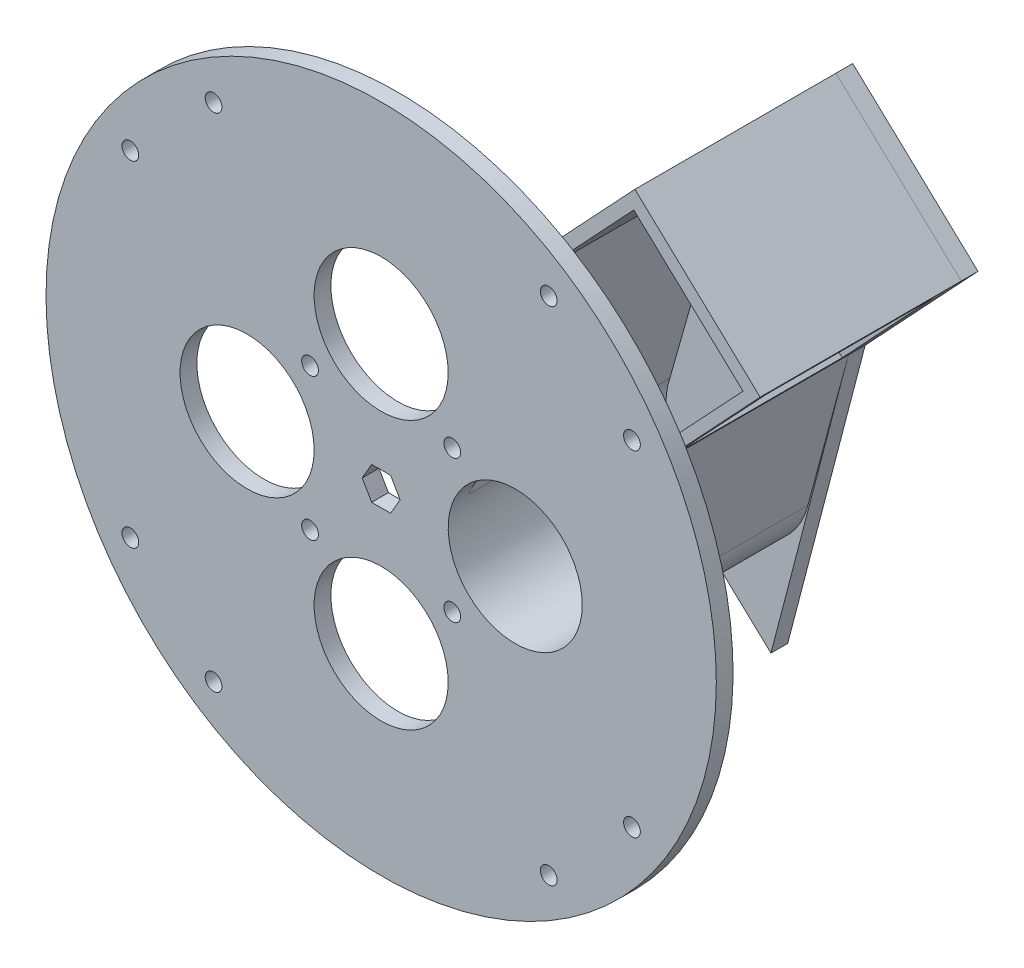
SolidWorks part; units mm, degrees
ref_plane "Front Plane" through (0, 0, 0) normal (0, 0, 1) x (1, 0, 0)
ref_plane "Top Plane" through (0, 0, 0) normal (0, 1, 0) x (1, 0, 0)
ref_plane "Right Plane" through (0, 0, 0) normal (1, 0, 0) x (0, 0, -1)
sketch "Sketch1" plane through (0, 0, 0) normal (0, 0, 1) x (1, 0, 0)
  line L1 (7.1857, 0) -> (3.5929, 6.223)
  line L2 (3.5929, 6.223) -> (-3.5929, 6.223)
  line L3 (-3.5929, 6.223) -> (-7.1857, 0)
  line L4 (-7.1857, 0) -> (-3.5929, -6.223)
  line L5 (-3.5929, -6.223) -> (3.5929, -6.223)
  line L6 (3.5929, -6.223) -> (7.1857, 0)
  circle A0 centre (0, 0) radius 127
  circle A2 centre (0, 50.8) radius 25.4
  circle A3 centre (50.8, 0) radius 25.4
  circle A4 centre (0, -50.8) radius 25.4
  circle A5 centre (-50.8, 0) radius 25.4
  circle A7 centre (0, 0) radius 203.2 construction
  circle A8 centre (0, 0) radius 6.223 construction
  point P14 (0, 0)
  dimension "D1" = 254
  dimension "D2" = 25.4
  dimension "D3" = 4
  dimension "2" = 50.8
  dimension "D4" = 12.446
  dimension "D5" = 406.4
extrude "Boss-Extrude1" add sketch "Sketch1" along normal blind 6.35
sketch "Sketch3" plane through (0, 0, 0) normal (0, 0, -1) x (-1, 0, 0)
  line L0 (-26.9408, -26.9408) -> (26.9408, 26.9408) construction
  line L1 (-26.9408, 26.9408) -> (26.9408, -26.9408) construction
  line L2 (-63.5, 95.0381) -> (0, 0) construction
  line L3 (0, 0) -> (63.5, 95.0381) construction
  circle A0 centre (-26.9408, 26.9408) radius 3.175
  circle A1 centre (26.9408, 26.9408) radius 3.175
  circle A2 centre (26.9408, -26.9408) radius 3.175
  circle A3 centre (-26.9408, -26.9408) radius 3.175
  circle A4 centre (-63.5, 95.0381) radius 3.175
  circle A5 centre (63.5, 95.0381) radius 3.175
  circle A6 centre (95.0381, 63.5) radius 3.175
  circle A7 centre (95.0381, -63.5) radius 3.175
  circle A8 centre (63.5, -95.0381) radius 3.175
  circle A9 centre (-63.5, -95.0381) radius 3.175
  circle A10 centre (-95.0381, -63.5) radius 3.175
  circle A11 centre (-95.0381, 63.5) radius 3.175
  point P29 (0, 0)
  dimension "D1" = 6.35
  dimension "D2" = 76.2
  dimension "D3" = 127
  dimension "D4" = 114.3
  dimension "D5" = 4
extrude "Cut-Extrude1" cut sketch "Sketch3" against normal blind 6.35
surface "Surface-Plane1"
sketch "Sketch4" plane through (0, 0, 0) normal (0, 0, -1) x (-1, 0, 0)
  line L0 (-61.255, 92.793) -> (-92.7297, 61.3201) construction
  line L1 (-63.5, 95.0381) -> (-95.3816, 63.1565) construction
  line L2 (-63.5, 95.0381) -> (-55.6363, 102.9018) construction
  line L3 (-95.3816, 63.1565) -> (-101.5673, 56.9708) construction
  line L4 (-101.5673, 56.9708) -> (-94.5022, 49.9057) construction
  line L5 (-94.5022, 49.9057) -> (-47.0312, 94.3686) construction
  line L6 (-47.0312, 94.3686) -> (-89.7897, 140.0199) construction
  line L7 (-89.7897, 140.0199) -> (-137.2607, 95.557) construction
  line L8 (-137.2607, 95.557) -> (-101.5673, 56.9708) construction
  line L9 (-47.0312, 94.3686) -> (-22.9112, 8.8206) construction
  line L10 (-15.8012, -16.3967) -> (-65.1502, -62.6185) construction
  line L11 (-79.1851, -7.0622) -> (-94.5022, 49.9057) construction
  line L12 (-22.9112, 8.8206) -> (-47.0312, 94.3686)
  line L13 (-47.0312, 94.3686) -> (-89.7897, 140.0199)
  line L14 (-89.7897, 140.0199) -> (-137.2607, 95.557)
  line L15 (-137.2607, 95.557) -> (-94.5022, 49.9057)
  line L16 (-94.5022, 49.9057) -> (-79.1851, -7.0622)
  line L18 (-75.0781, -7.4654) -> (-91.6903, 52.5394)
  line L19 (-91.6903, 52.5394) -> (-130.775, 94.2684)
  line L20 (-26.858, 8.4817) -> (-50.3033, 91.3037)
  line L21 (-50.3033, 91.3037) -> (-89.3881, 133.0328)
  line L22 (-89.3881, 133.0328) -> (-130.775, 94.2684)
  circle A0 centre (-63.5, 95.0381) radius 3.175 construction
  circle A1 centre (-95.0381, 63.5) radius 3.175 construction
  circle A2 centre (-50.8, 0) radius 25.4 construction
  arc A3 (-75.4608, -6.0832) -> (-26.858, 8.4817) centre (-50.8, 0) ccw
  arc A4 (-79.1851, -7.0622) -> (-22.9112, 8.8206) centre (-50.8, 0) ccw
  point P31 (0, 0)
  point P32 (-22.7548, 8.6577)
extrude "Boss-Extrude3" add sketch "Sketch4" along normal blind 76.2
ref_plane "Plane1" through (0, 0, -76.2) normal (0, 0, -1) x (-1, 0, 0)
sketch "Sketch8" plane through (25.4404, -23.8283, 0) normal (0.7299, -0.6836, 0) x (0, 0, -1)
  line L0 (0, 163.5746) -> (76.2, 101.0259) construction
  line L1 (76.2, -63.6411) -> (76.2, 63.6411) construction
  line L2 (76.2, 101.0259) -> (0, 101.0259) construction
  line L3 (38.1, 101.0259) -> (38.1, 163.5746) construction
  line L4 (76.2, 163.5746) -> (0, 163.5746) construction
  line L5 (76.2, 163.5746) -> (0, 101.0259) construction
  line L7 (6.35, 157.7002) -> (69.85, 157.7002)
  line L8 (6.35, 157.7002) -> (6.35, 106.9002)
  line L9 (6.35, 106.9002) -> (69.85, 106.9002)
  line L10 (69.85, 157.7002) -> (69.85, 106.9002)
  line L11 (6.35, 157.7002) -> (69.85, 106.9002) construction
  line L12 (6.35, 106.9002) -> (69.85, 157.7002) construction
  point P14 (38.1, 132.3002)
  dimension "D1" = 63.5
  dimension "D2" = 50.8
extrude "Cut-Extrude2" cut sketch "Sketch8" against normal blind 6.35
sketch "Sketch6" plane through (0, 0, -76.2) normal (0, 0, -1) x (-1, 0, 0)
  line L6 (-47.0312, 94.3686) -> (-89.7897, 140.0199) construction
  line L7 (-89.7897, 140.0199) -> (-137.2607, 95.557) construction
  line L9 (-47.0312, 94.3686) -> (-15.8012, -16.3967) construction
  line L10 (-15.8012, -16.3967) -> (-65.1502, -62.6185) construction
  line L11 (-65.1502, -62.6185) -> (-94.5022, 49.9057) construction
  line L12 (-15.8012, -16.3967) -> (-47.0312, 94.3686)
  line L13 (-47.0312, 94.3686) -> (-89.7897, 140.0199)
  line L14 (-89.7897, 140.0199) -> (-137.2607, 95.557)
  line L15 (-137.2607, 95.557) -> (-94.5022, 49.9057)
  line L16 (-94.5022, 49.9057) -> (-65.1502, -62.6185)
  line L17 (-65.1502, -62.6185) -> (-15.8012, -16.3967)
extrude "Boss-Extrude4" add sketch "Sketch6" along normal blind 6.35 separate body
ref_plane "Plane2" through (75.6175, -20.3313, 0) normal (0.9657, -0.2596, 0) x (0, 0, -1)
sketch "Sketch10" plane through (75.6175, -20.3313, 0) normal (0.9657, -0.2596, 0) x (0, 0, -1)
  line L0 (31.6202, -19.7099) -> (76.2, 72.7315) construction
  point P2 (76.1227, 72.7125)
  point P3 (34.2564, -35.5849)
  point P4 (77.0196, 72.6402)
  point P6 (31.6202, -19.7099)
ref_plane "Plane3" through (0, 0, -76.2) normal (0, 0, -1) x (-1, 0, 0)
